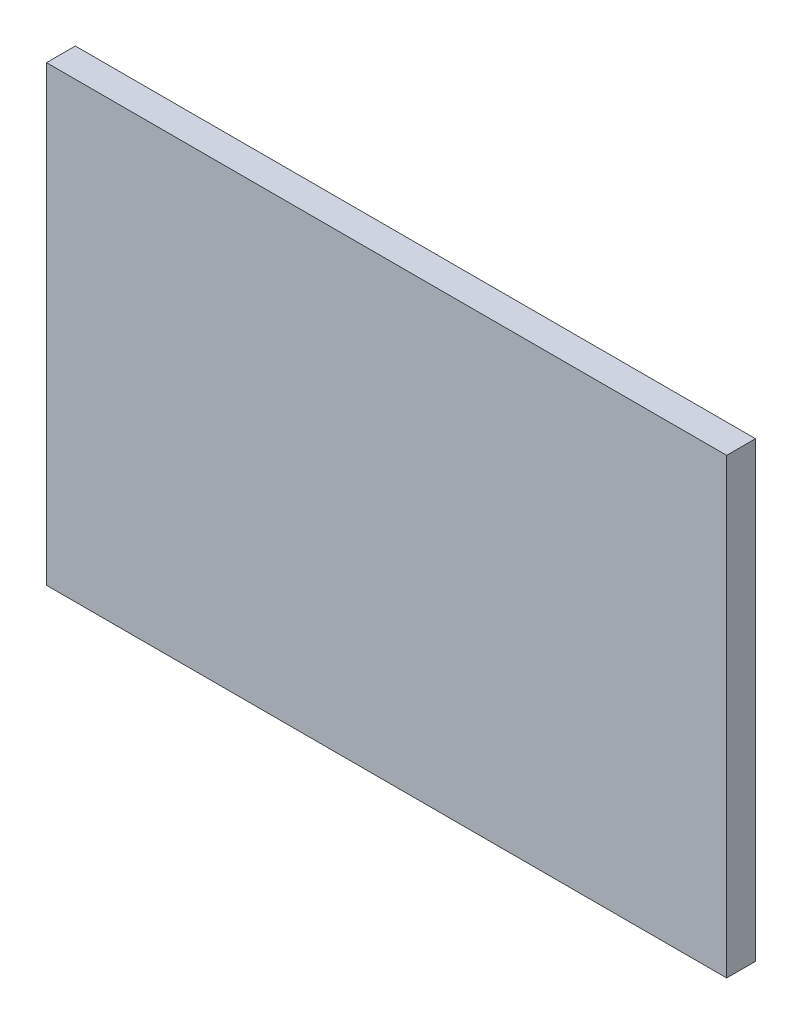
SolidWorks part; units mm, degrees
material "Пластичное железо (SN)"
ref_plane "Спереди" through (0, 0, 0) normal (0, 0, 1) x (1, 0, 0)
ref_plane "Сверху" through (0, 0, 0) normal (0, 1, 0) x (1, 0, 0)
ref_plane "Справа" through (0, 0, 0) normal (1, 0, 0) x (0, 0, -1)
sketch "Эскиз1" plane through (0, 0, 0) normal (0, 0, 1) x (1, 0, 0)
  line L1 (42.48, -28.27) -> (-42.48, -28.27)
  line L2 (42.48, -28.27) -> (42.48, 28.27)
  line L3 (42.48, 28.27) -> (-42.48, 28.27)
  line L4 (-42.48, -28.27) -> (-42.48, 28.27)
  line L5 (42.48, -28.27) -> (-42.48, 28.27) construction
  line L6 (42.48, 28.27) -> (-42.48, -28.27) construction
  point P0 (0, 0)
  point P6 (-92.3442, -58.9829)
extrude "Бобышка-Вытянуть1" add sketch "Эскиз1" along normal blind 3.6
